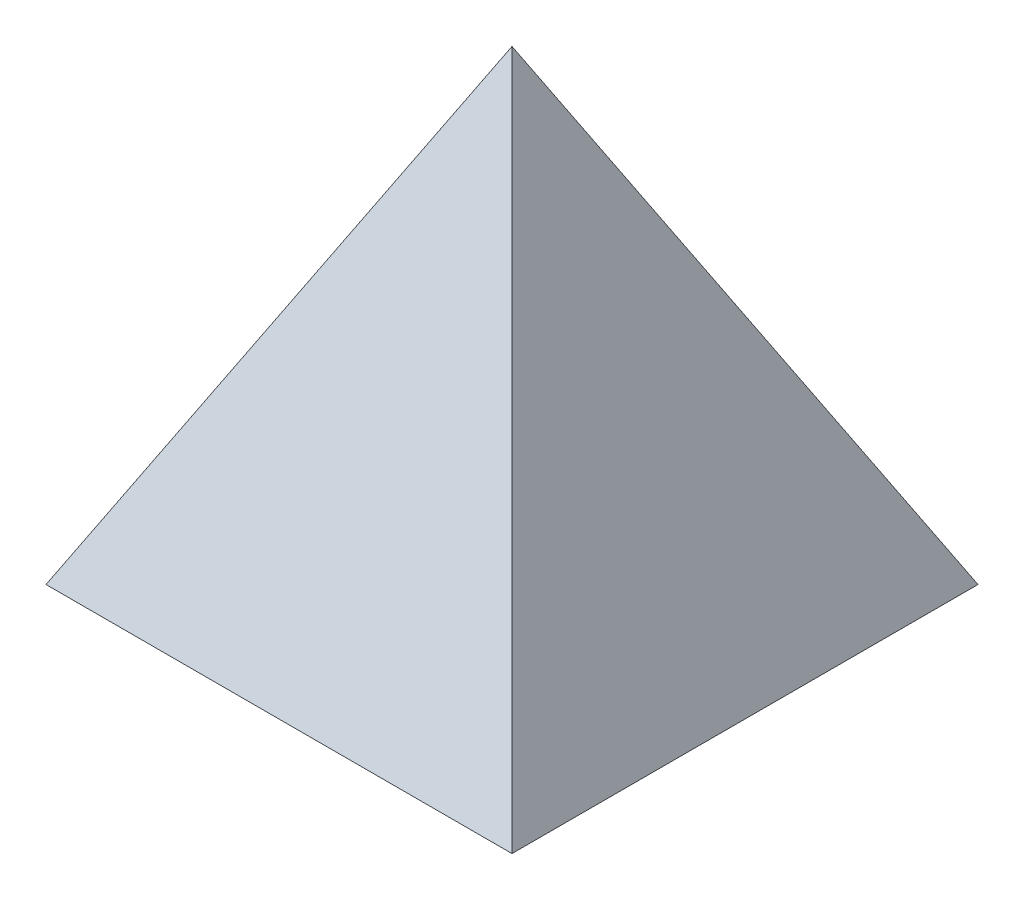
SolidWorks part; units mm, degrees
ref_plane "Front Plane" through (0, 0, 0) normal (0, 0, 1) x (1, 0, 0)
ref_plane "Top Plane" through (0, 0, 0) normal (0, 1, 0) x (1, 0, 0)
ref_plane "Right Plane" through (0, 0, 0) normal (1, 0, 0) x (0, 0, -1)
sketch "Sketch1" plane through (0, 0, 0) normal (0, 1, 0) x (1, 0, 0)
  line L1 (0, 0) -> (0.6, 0)
  line L2 (0, 0) -> (0, 0.6)
  line L3 (0, 0.6) -> (0.6, 0.6)
  line L4 (0.6, 0) -> (0.6, 0.6)
  dimension "D1" = 0.6
  dimension "D2" = 0.6
extrude "Boss-Extrude1" add sketch "Sketch1" along normal blind 0.6
sketch "Sketch2" plane through (0, 0, 0) normal (0, 0, 1) x (1, 0, 0)
  line L0 (0.3, 0.6) -> (0, 0)
  line L1 (0, 0.6) -> (0.6, 0.6) construction
  line L2 (0, 0) -> (0, 0.6)
  line L3 (0, 0.6) -> (0.3, 0.6)
  line L4 (0.6, 0) -> (0.3, 0.6)
  line L5 (0.6, 0.6) -> (0.6, 0)
  line L6 (0.3, 0.6) -> (0.6, 0.6)
extrude "Cut-Extrude1" cut sketch "Sketch2" against normal blind 0.6 contours L3 L2 L0 | L6 L4 L5
sketch "Sketch3" plane through (0, 0, 0) normal (1, 0, 0) x (0, 0, -1)
  line L0 (0.6, 0) -> (0.3, 0.6)
  line L1 (0.6, 0.6) -> (0, 0.6) construction
  line L2 (0.3, 0.6) -> (0.6, 0.6)
  line L3 (0.6, 0.6) -> (0.6, 0)
  line L4 (0.3, 0.6) -> (0, 0)
  line L5 (0, 0) -> (0, 0.6)
  line L6 (0, 0.6) -> (0.3, 0.6)
extrude "Cut-Extrude4" cut sketch "Sketch3" along normal blind 0.6 contours L3 L2 L0 | L6 L5 L4
